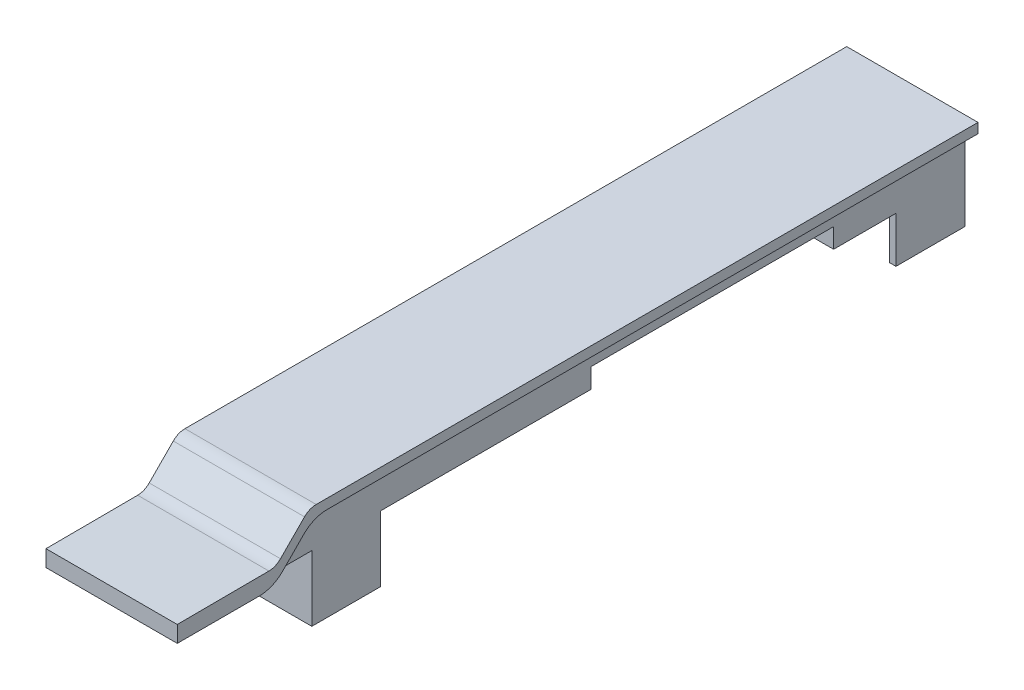
SolidWorks part; units mm, degrees
ref_plane "Front Plane" through (0, 0, 0) normal (0, 0, 1) x (1, 0, 0)
ref_plane "Top Plane" through (0, 0, 0) normal (0, 1, 0) x (1, 0, 0)
ref_plane "Right Plane" through (0, 0, 0) normal (1, 0, 0) x (0, 0, -1)
sketch "Sketch1" plane through (0, 0, 0) normal (1, 0, 0) x (0, 0, -1)
  line L0 (0, 0) -> (-130, 0)
  line L1 (0, 0) -> (74, 0) construction
  line L2 (0, 0) -> (0, 6)
  line L3 (0, 6) -> (74, 6)
  line L4 (74, 6) -> (74, 0)
  line L5 (74, 0) -> (114, 0)
  line L6 (-130, 0) -> (-130, 5)
  line L7 (-130, 5) -> (-100.0004, 5.1483)
  line L8 (-100.0004, 5.1483) -> (-89.7505, 15.5)
  line L11 (114, 15.5) -> (-89.7505, 15.5)
  line L12 (114, 0) -> (114, 15.5)
  dimension "D1" = 130
  dimension "D2" = 74
  dimension "D3" = 6
  dimension "D4" = 40
  dimension "D5" = 30
  dimension "D6" = 5
  dimension "D7" = 135
  dimension "D8" = 9.5
extrude "Boss-Extrude1" add sketch "Sketch1" along normal blind 40
sketch "Sketch4" plane through (40, 0, 0) normal (1, 0, 0) x (0, 0, -1)
  line L11 (-130, 0) -> (0, 0) construction
  line L12 (-130, 0) -> (0, 0) construction
  line L13 (-100.8762, 0) -> (0, 0)
  line L14 (0, 0) -> (111, 0)
  line L15 (74, 0) -> (114, 0) construction
  line L16 (111, 0) -> (111, 3)
  line L22 (-3, 3) -> (-3, 9)
  line L23 (-3, 9) -> (77, 9)
  line L24 (77, 9) -> (77, 3)
  line L25 (77, 3) -> (111, 3)
  line L26 (111, 3) -> (111, 12.5)
  line L28 (111, 12.5) -> (-88.4991, 12.5)
  line L29 (-88.4991, 12.5) -> (-97.9057, 3)
  line L30 (-97.9057, 3) -> (-3, 3)
  line L35 (111, 3) -> (111, 12.5)
  line L37 (111, 12.5) -> (-88.4991, 12.5)
  line L38 (-88.4991, 12.5) -> (-100.8762, 0)
  dimension "D1" = 3
ref_plane "Plane1" through (20, 0, 0) normal (1, 0, 0) x (0, 0, -1)
sketch "Sketch5" plane through (20, 0, 0) normal (1, 0, 0) x (0, 0, -1)
  line L0 (-117.866, 5.06) -> (-112.2372, 10.7447)
  line L1 (-100.0004, 5.1483) -> (-130, 5) construction
  line L2 (-89.7505, 15.5) -> (-100.0004, 5.1483) construction
  line L3 (-112.2372, 10.7447) -> (-81.8129, 10.7447)
  line L4 (-117.866, 5.06) -> (-95.866, 5.06)
  line L6 (-81.8129, 10.7447) -> (-95.866, 5.06)
  line L11 (-88.4991, 12.5) -> (-100.8762, 0) construction
  dimension "D1" = 22
  dimension "D2" = 8
sketch "Sketch6" plane through (40, 0, 0) normal (1, 0, 0) x (0, 0, -1)
  line L0 (-130, 0) -> (114, 0) construction
  line L1 (74, 0) -> (114, 0) construction
  line L2 (114, 0) -> (114, 15.5) construction
  line L3 (-100.8762, 0) -> (114, 0)
  line L4 (114, 0) -> (114, 12.5)
  line L20 (-3, 3) -> (-3, 9)
  line L21 (-3, 9) -> (77, 9)
  line L22 (77, 9) -> (77, 3)
  line L23 (77, 3) -> (111, 3)
  line L24 (111, 3) -> (111, 12.5)
  line L25 (111, 12.5) -> (-88.4991, 12.5)
  line L26 (-88.4991, 12.5) -> (-97.9057, 3)
  line L27 (-97.9057, 3) -> (-3, 3)
  line L33 (114, 12.5) -> (-88.4991, 12.5)
  line L34 (-88.4991, 12.5) -> (-100.8762, 0)
  dimension "D1" = 3
extrude "Cut-Extrude2" cut sketch "Sketch6" against normal blind 4
mirror "Mirror3" about plane through (20, 0, 0) normal (1, 0, 0) of "Cut-Extrude2"
fillet "Fillet6" radius 10 4 edges at (2, 12.5, 88.4991) (2, 0, 100.8762) (38, 0, 100.8762) (38, 12.5, 88.4991)
fillet "Fillet7" radius 5 2 edges at (20, 15.5, 89.7505) (20, 5.1483, 100.0004)
sketch "Sketch7" plane through (0, 0, 0) normal (0, -1, 0) x (1, 0, 0)
  line L0 (20, 130) -> (20, 85) construction
  line L1 (40, 130) -> (0, 130) construction
  line L2 (36, 85) -> (4, 85)
  line L3 (4, 105.0473) -> (4, 0) construction
  line L4 (4, 85) -> (4, 64)
  line L5 (4, 64) -> (6, 64)
  line L6 (6, 64) -> (6, 83)
  line L7 (6, 83) -> (34, 83)
  line L8 (34, 64) -> (34, 83)
  line L9 (36, 64) -> (34, 64)
  line L10 (36, 85) -> (36, 64)
  point P11 (11.5, 65.3016)
  point P13 (20, 83)
  point P16 (4, 65.8572)
  dimension "D1" = 45
  dimension "D2" = 21
  dimension "D3" = 2
  dimension "D4" = 2
extrude "Boss-Extrude2" add sketch "Sketch7" along normal blind 20
sketch "Sketch8" plane through (0, 0, 85) normal (0, 0, 1) x (1, 0, 0)
  line L0 (15.75, -8.75) -> (21, -8.75) construction
  line L1 (15.75, -8.75) -> (15.75, -5) construction
  line L2 (12.5, -20) -> (12.5, -5) construction
  line L3 (0, -12.5) -> (25, -12.5) construction
  line L4 (4, -20) -> (21, -20) construction
  line L5 (21, -20) -> (4, -20) construction
  line L6 (36, -20) -> (4, -20) construction
  line L7 (9.25, -16.25) -> (9.25, -20) construction
  line L8 (9.25, -16.25) -> (4, -16.25) construction
  line L9 (4, -20) -> (4, 0) construction
  circle A0 centre (15.75, -16.25) radius 1.6
  circle A1 centre (9.25, -16.25) radius 1.6
  circle A2 centre (9.25, -8.75) radius 1.6
  circle A3 centre (15.75, -8.75) radius 1.6
  circle A4 centre (9.25, -16.25) radius 3 construction
  dimension "D3" = 3.2
  dimension "D1" = 3.75
  dimension "D2" = 5.25
extrude "Cut-Extrude3" [suppressed] cut sketch "Sketch8" against normal up to surface (2 mm away)
sketch "Sketch9" plane through (0, 0, 0) normal (0, -1, 0) x (1, 0, 0)
  line L0 (4, -114) -> (36, -114)
  line L1 (36, -114) -> (4, -114) construction
  line L2 (36, -114) -> (36, 84.328) construction
  line L3 (36, -74) -> (36, -114) construction
  line L4 (36, -114) -> (36, -93)
  line L5 (36, -93) -> (34, -93)
  line L6 (34, -93) -> (34, -112)
  line L7 (34, -112) -> (6, -112)
  line L8 (20, -114) -> (20, -112) construction
  line L9 (6, -93) -> (6, -112)
  line L10 (4, -93) -> (6, -93)
  line L11 (4, -114) -> (4, -93)
  dimension "D1" = 21
  dimension "D2" = 2
  dimension "D3" = 2
extrude "Boss-Extrude3" add sketch "Sketch9" along normal blind 14 contours L9 L7 L6 L5 L4 L0 L11 L10
sketch "Sketch11" plane through (0, 0, -114) normal (0, 0, -1) x (-1, 0, 0)
  line L2 (-12.5, -14) -> (-12.5, 1) construction
  line L3 (-25, -6.5) -> (0, -6.5) construction
  line L4 (-21, -14) -> (-4, -14) construction
  line L5 (-4, -14) -> (-21, -14) construction
  line L6 (-15.75, -10.25) -> (-15.75, -14) construction
  line L7 (-15.75, -10.25) -> (-21, -10.25) construction
  line L8 (-4, -14) -> (-21, -14) construction
  line L9 (-4, -14) -> (-36, -14) construction
  line L10 (-4, -14) -> (-4, 12.5) construction
  circle A0 centre (-9.25, -10.25) radius 1.6
  circle A1 centre (-15.75, -10.25) radius 1.6
  circle A4 centre (-15.75, -10.25) radius 3 construction
  dimension "D3" = 3.2
  dimension "D1" = 5.25
  dimension "D2" = 3.75
extrude "Cut-Extrude4" [suppressed] cut sketch "Sketch11" against normal up to surface (2 mm away)
